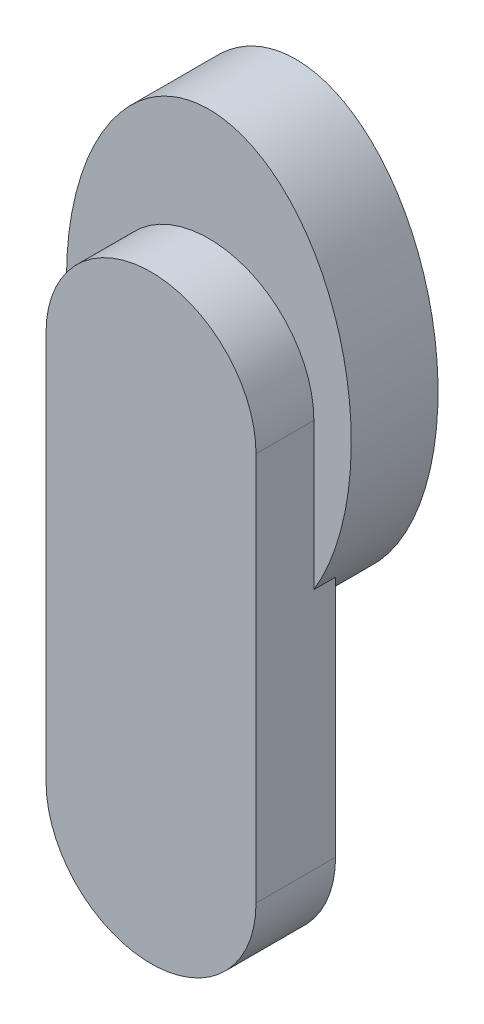
SolidWorks part; units mm, degrees
ref_plane "前视基准面" through (0, 0, 0) normal (0, 0, 1) x (1, 0, 0)
ref_plane "上视基准面" through (0, 0, 0) normal (0, 1, 0) x (1, 0, 0)
ref_plane "右视基准面" through (0, 0, 0) normal (1, 0, 0) x (0, 0, -1)
other "Configuration Table"
sketch "草图1" plane through (0, 0, 0) normal (0, 0, 1) x (1, 0, 0)
  line L0 (0, 0) -> (0, -69.0508) construction
  circle A0 centre (0, 0) radius 30 construction
  ellipse E0 centre (0, 0) end of major axis (0, -30) minor radius 19.6915
extrude "凸台-拉伸1" add sketch "草图1" along normal blind 10 and the other way blind 2
sketch "草图2" plane through (0, 0, 10) normal (0, 0, 1) x (1, 0, 0)
  line L0 (0, 0) -> (0, -53.812) construction
  line L1 (14.5182, 0) -> (14.5182, -53.812)
  line L2 (-14.5182, 0) -> (-14.5182, -53.812)
  arc A0 (14.5182, 0) -> (-14.5182, 0) centre (0, 0) ccw
  arc A1 (-14.5182, -53.812) -> (14.5182, -53.812) centre (0, -53.812) ccw
  circle A2 centre (0, -54.812) radius 1 construction
  point P3 (0, -26.906)
  point P8 (0, -72.805)
extrude "凸台-拉伸2" add sketch "草图2" along normal blind 8 and the other way blind 3
